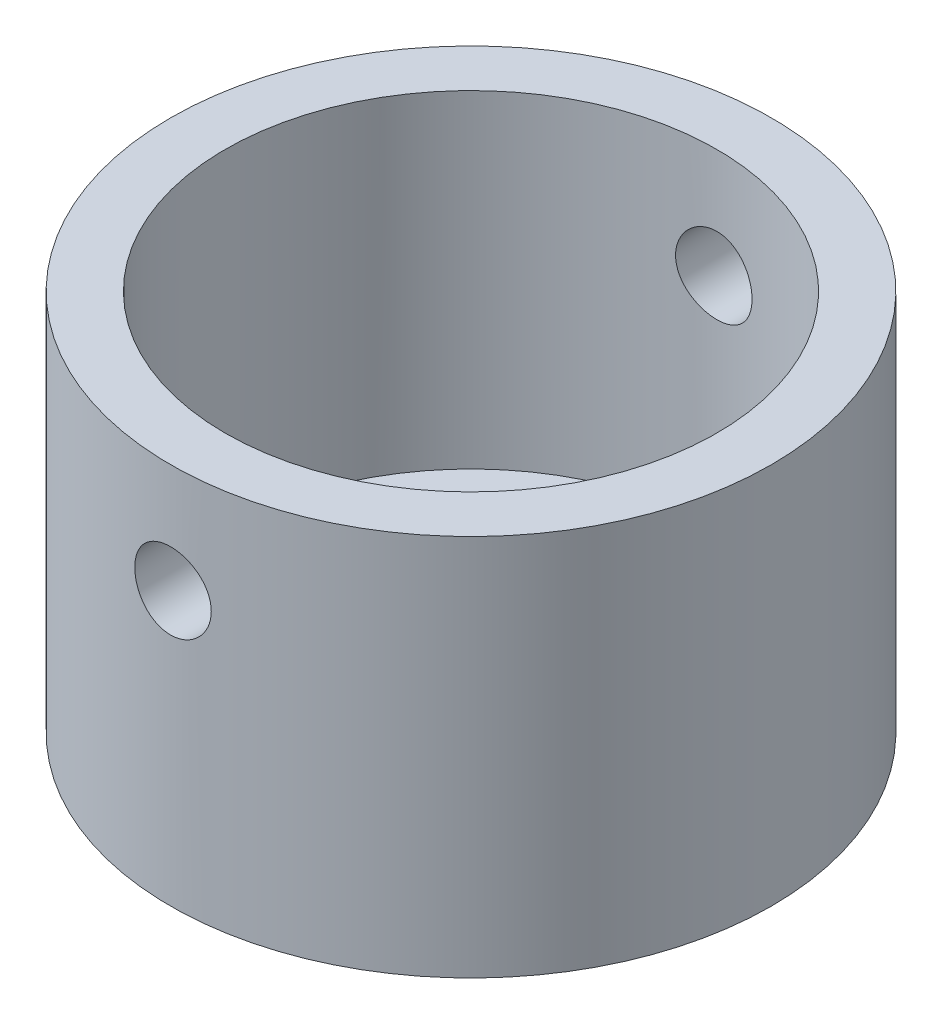
SolidWorks part; units mm, degrees
ref_plane "Front Plane" through (0, 0, 0) normal (0, 0, 1) x (1, 0, 0)
ref_plane "Top Plane" through (0, 0, 0) normal (0, 1, 0) x (1, 0, 0)
ref_plane "Right Plane" through (0, 0, 0) normal (1, 0, 0) x (0, 0, -1)
sketch "Sketch1" plane through (0, 0, 0) normal (0, 1, 0) x (1, 0, 0)
  circle A0 centre (0, 0) radius 22.5
  dimension "D1" = 45
extrude "Extrude-Thin1" add sketch "Sketch1" along normal blind 10 and the other way blind 25 thin contours A0
ref_plane "Plane1" through (0, 0, 27.5) normal (0, 0, 1) x (1, 0, 0)
sketch "Sketch2" plane through (0, 0, 27.5) normal (0, 0, 1) x (1, 0, 0)
  circle A0 centre (0, 0) radius 3.5
extrude "Cut-Extrude1" cut sketch "Sketch2" against normal up to surface (5.2739 mm away) contours A0
mirror "Mirror1" about plane through (0, 0, 0) normal (0, 0, 1) of "Cut-Extrude1"
sketch "Sketch3" plane through (0, -25, 0) normal (0, -1, 0) x (1, 0, 0)
  circle A0 centre (0, 0) radius 22.5
extrude "Boss-Extrude1" add sketch "Sketch3" against normal blind 5
